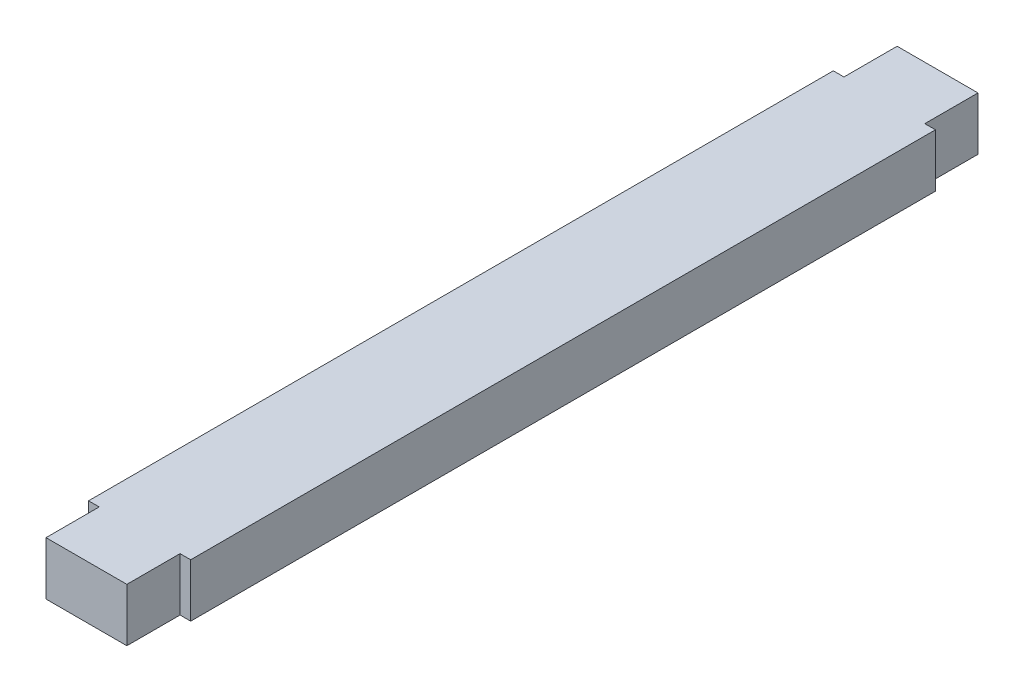
SolidWorks part; units mm, degrees
material "Pine"
ref_plane "Front Plane" through (0, 0, 0) normal (0, 0, 1) x (1, 0, 0)
ref_plane "Top Plane" through (0, 0, 0) normal (0, 1, 0) x (1, 0, 0)
ref_plane "Right Plane" through (0, 0, 0) normal (1, 0, 0) x (0, 0, -1)
sketch "Sketch1" plane through (0, 0, 0) normal (0, 1, 0) x (1, 0, 0)
  line L0 (0, 0) -> (0, 17.78)
  line L1 (0, 17.78) -> (-1.27, 17.78)
  line L2 (-1.27, 17.78) -> (-1.27, 24.13)
  line L3 (-1.27, 24.13) -> (-10.922, 24.13)
  line L4 (-10.922, 24.13) -> (-10.922, 17.78)
  line L5 (-10.922, 17.78) -> (-12.192, 17.78)
  line L6 (-12.192, 17.78) -> (-12.192, 0)
  line L12 (-12.192, -53.34) -> (-12.192, -71.12)
  line L14 (0, -71.12) -> (0, -53.34)
  line L18 (-12.192, -71.12) -> (-10.922, -71.12)
  line L19 (-10.922, -71.12) -> (-10.922, -77.47)
  line L20 (-10.922, -77.47) -> (-1.27, -77.47)
  line L21 (-1.27, -77.47) -> (-1.27, -71.12)
  line L22 (-1.27, -71.12) -> (0, -71.12)
  line L24 (-12.192, 0) -> (-12.192, -53.34)
  line L25 (0, 0) -> (0, -53.34)
  dimension "D5" = 1.27
  dimension "D9" = 1.27
  dimension "D1" = 12.192
  dimension "D2" = 17.78
  dimension "D3" = 9.652
  dimension "D4" = 1.27
  dimension "D6" = 17.78
  dimension "D7" = 53.34
  dimension "D8" = 17.78
  dimension "D10" = 6.35
  dimension "D11" = 6.35
extrude "Boss-Extrude1" add sketch "Sketch1" along normal blind 6.35
